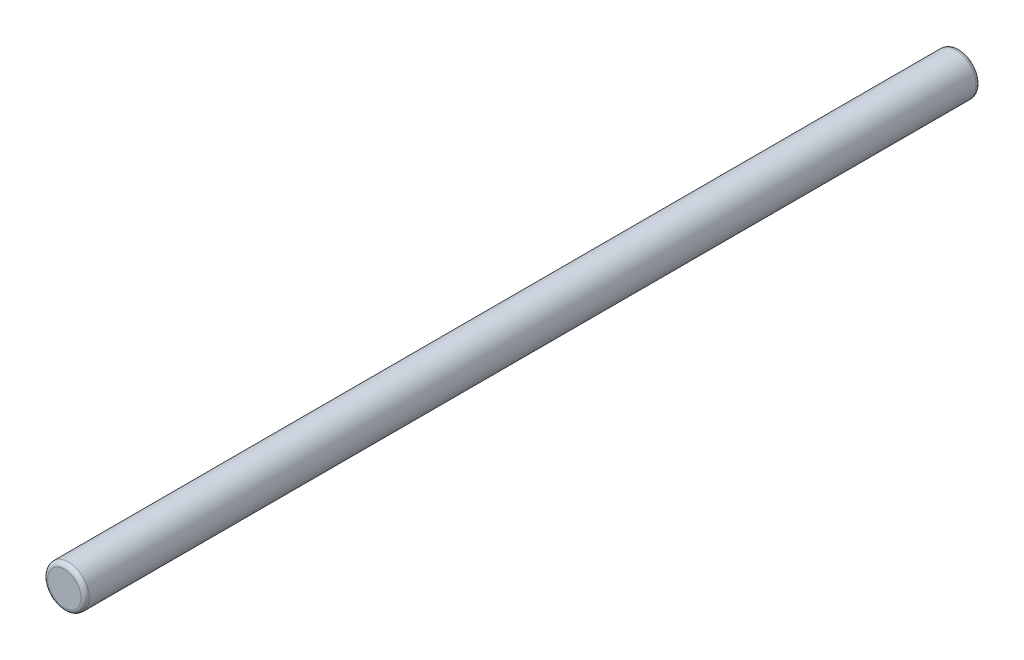
SolidWorks part; units mm, degrees
material "Простая углеродистая сталь"
ref_plane "Спереди" through (0, 0, 0) normal (0, 0, 1) x (1, 0, 0)
ref_plane "Сверху" through (0, 0, 0) normal (0, 1, 0) x (1, 0, 0)
ref_plane "Справа" through (0, 0, 0) normal (1, 0, 0) x (0, 0, -1)
sketch "Эскиз1" plane through (0, 0, 0) normal (0, 0, 1) x (1, 0, 0)
  circle A0 centre (0, 0) radius 1
  dimension "D1" = 2
extrude "Бобышка-Вытянуть1" add sketch "Эскиз1" along normal blind 43
fillet "Скругление1" radius 0.2 2 edges at (1, 0, 0) (1, 0, 43)
